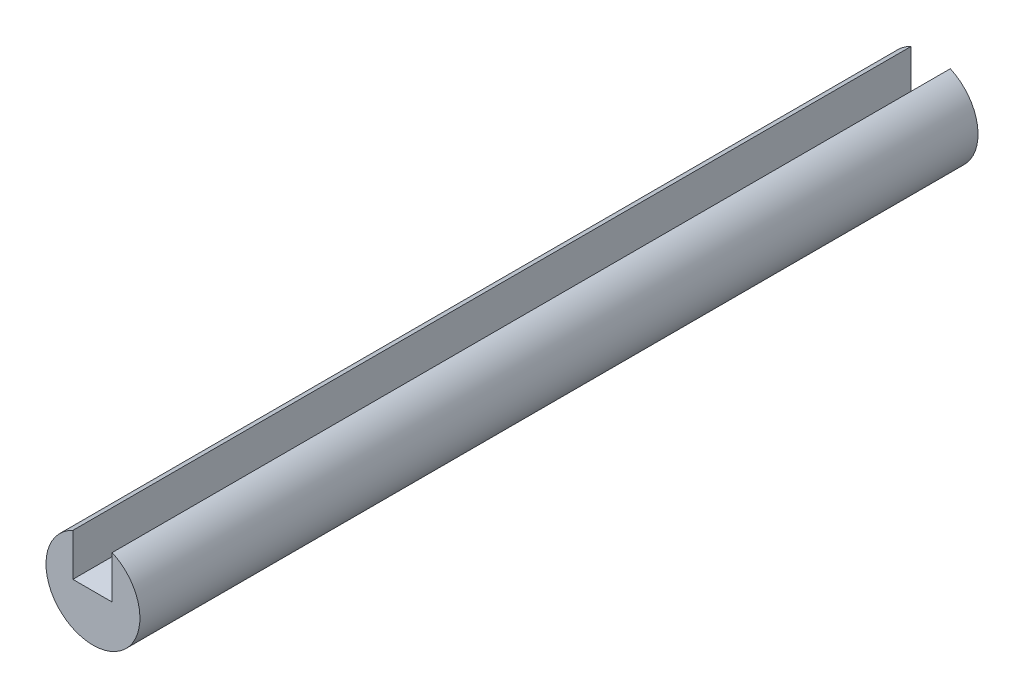
SolidWorks part; units mm, degrees
material "Alloy Steel"
ref_plane "Front Plane" through (0, 0, 0) normal (0, 0, 1) x (1, 0, 0)
ref_plane "Top Plane" through (0, 0, 0) normal (0, 1, 0) x (1, 0, 0)
ref_plane "Right Plane" through (0, 0, 0) normal (1, 0, 0) x (0, 0, -1)
sketch "Sketch1" plane through (0, 0, 0) normal (0, 0, 1) x (1, 0, 0)
  circle A0 centre (0, 0) radius 4.7625
  dimension "D1" = 9.525
extrude "Boss-Extrude1" add sketch "Sketch1" along normal blind 80 and the other way blind 5
sketch "Sketch2" plane through (0, 0, 80) normal (0, 0, 1) x (1, 0, 0)
  line L0 (0, 0) -> (1.9501, 0)
  line L1 (1.9501, 0) -> (1.9501, 10.0041)
  line L2 (1.9501, 10.0041) -> (-2.0395, 10.0041)
  line L3 (-2.0395, 10.0041) -> (-2.0395, 0)
  line L4 (-2.0395, 0) -> (0, 0)
extrude "Cut-Extrude2" cut sketch "Sketch2" against normal blind 85
